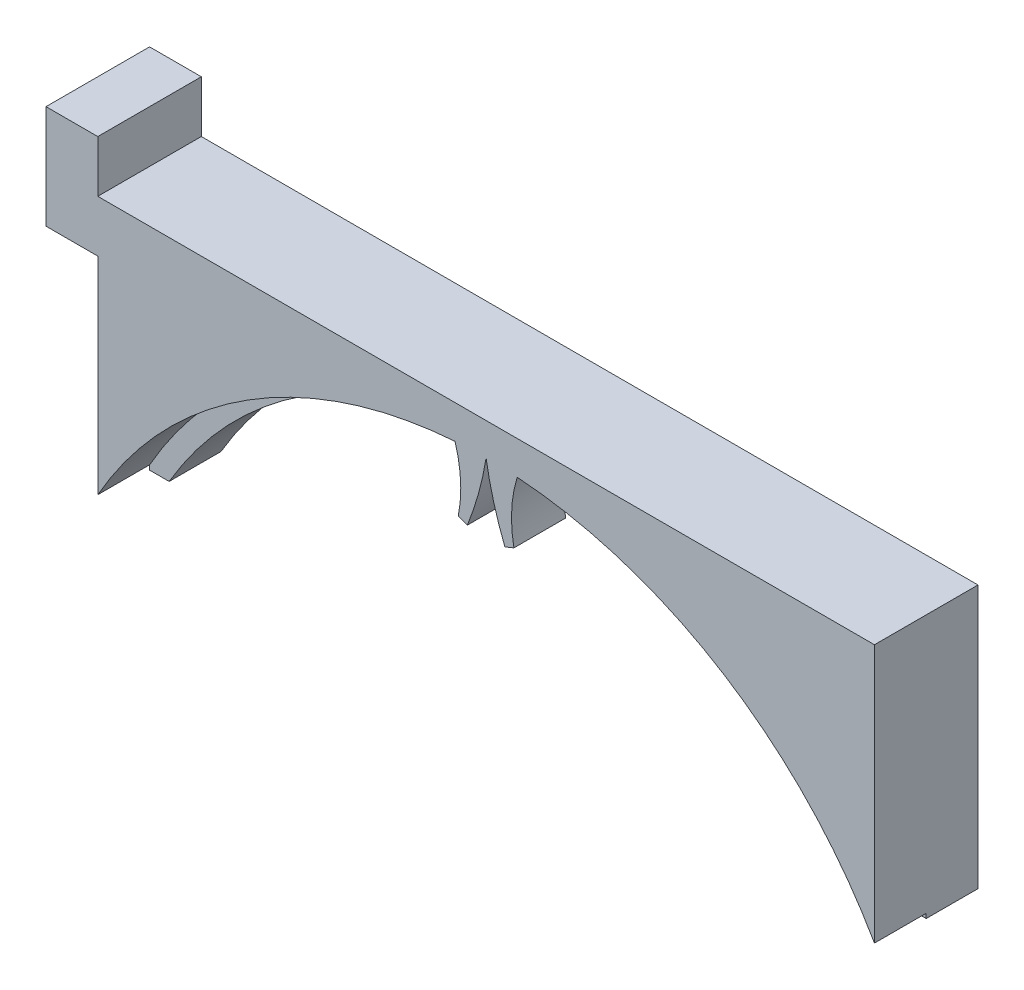
SolidWorks part; units mm, degrees
ref_plane "Front Plane" through (0, 0, 0) normal (0, 0, 1) x (1, 0, 0)
ref_plane "Top Plane" through (0, 0, 0) normal (0, 1, 0) x (1, 0, 0)
ref_plane "Right Plane" through (0, 0, 0) normal (1, 0, 0) x (0, 0, -1)
sketch "Sketch1" plane through (0, 0, 0) normal (0, 0, 1) x (1, 0, 0)
  line L0 (0, 0) -> (0, -92.55) construction
  line L1 (-75, 0) -> (75, 0)
  line L2 (-75, 0) -> (-75, -50.8)
  line L3 (-75, -50.8) -> (-71.214, -50.8)
  line L4 (75, 0) -> (75, -50.8)
  line L5 (71.214, -50.8) -> (75, -50.8)
  arc A0 (71.214, -50.8) -> (-71.214, -50.8) centre (0, -92.55) ccw
  point P8 (0, -10)
  dimension "D3" = 165.1
  dimension "D1" = 50.8
  dimension "D2" = 150
  dimension "D4" = 10
extrude "Boss-Extrude1" add sketch "Sketch1" along normal blind 10
sketch "Sketch2" plane through (0, 0, 10) normal (0, 0, 1) x (1, 0, 0)
  line L0 (0, -6.2777) -> (-3.6276, -19.3188) construction
  line L1 (0, -6.2777) -> (3.6276, -19.3188) construction
  line L2 (0, 0) -> (0, -92.55) construction
  line L3 (-3.6276, -19.3188) -> (3.6276, -19.3188) construction
  line L5 (-6, -6.4866) -> (0, -6.2777) construction
  line L6 (0, -6.2777) -> (6, -6.4866) construction
  line L8 (75, 0) -> (75, -49.913)
  line L9 (75, -50.8) -> (75, 0) construction
  line L10 (75, 0) -> (-75, 0)
  line L11 (-75, 0) -> (-75, -49.913)
  line L12 (-75, 0) -> (-75, -50.8) construction
  line L13 (-3.6276, -19.3188) -> (-5.3686, -18.6229)
  line L14 (3.6276, -19.3188) -> (5.3686, -18.6229)
  arc A0 (0, -6.2777) -> (-3.6276, -19.3188) centre (-61.4292, 3.7848) cw
  circle A1 centre (0, -92.55) radius 86.2723 construction
  arc A2 (71.214, -50.8) -> (-71.214, -50.8) centre (0, -92.55) ccw construction
  arc A3 (0, -6.2777) -> (3.6276, -19.3188) centre (61.4292, 3.7848) ccw
  arc A6 (-6, -6.4866) -> (-75, -49.913) centre (0, -92.55) ccw
  arc A7 (75, -49.913) -> (6, -6.4866) centre (0, -92.55) ccw
  arc A8 (-6, -6.4866) -> (-5.3686, -18.6229) centre (-29.6489, -13.8016) cw
  arc A9 (5.3686, -18.6229) -> (6, -6.4866) centre (29.6489, -13.8016) cw
  point P6 (0, -19.3188)
  point P29 (0, 0)
  point P31 (0, 0)
  point P32 (0, -91.7218)
  point P35 (0, -10)
  dimension "D2" = 12
  dimension "D3" = 10
extrude "Boss-Extrude2" add sketch "Sketch2" along normal blind 10
sketch "Sketch3" plane through (0, 0, 20) normal (0, 0, 1) x (1, 0, 0)
  line L0 (-75, 0) -> (-75, -49.913) construction
  line L1 (-85, 10) -> (-75, 10)
  line L2 (-85, 10) -> (-85, -10)
  line L3 (-85, -10) -> (-75, -10)
  line L4 (-75, 10) -> (-75, -10)
  line L5 (75, 0) -> (-75, 0) construction
  dimension "D1" = 10
  dimension "D2" = 20
  dimension "D3" = 10
extrude "Boss-Extrude3" add sketch "Sketch3" against normal blind 20
